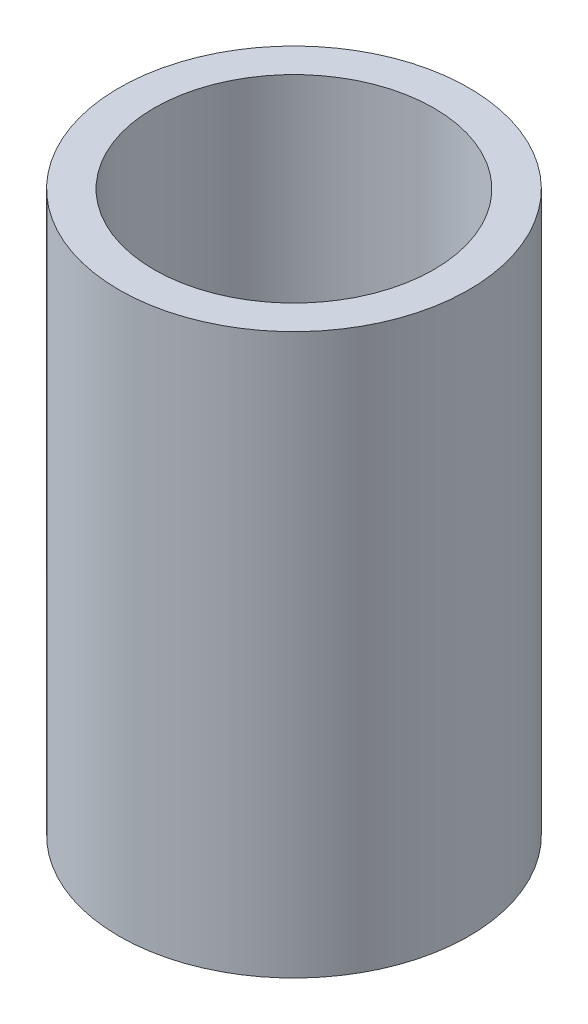
SolidWorks part; units mm, degrees
ref_plane "Front Plane" through (0, 0, 0) normal (0, 0, 1) x (1, 0, 0)
ref_plane "Top Plane" through (0, 0, 0) normal (0, 1, 0) x (1, 0, 0)
ref_plane "Right Plane" through (0, 0, 0) normal (1, 0, 0) x (0, 0, -1)
sketch "Sketch2" plane through (0, 0, 0) normal (0, 1, 0) x (1, 0, 0)
  circle A0 centre (0, 0) radius 15.875
  circle A2 centre (0, 0) radius 12.7
  dimension "D1" = 31.75
  dimension "D2" = 25.4
extrude "Boss-Extrude1" add sketch "Sketch2" along normal blind 50.8
